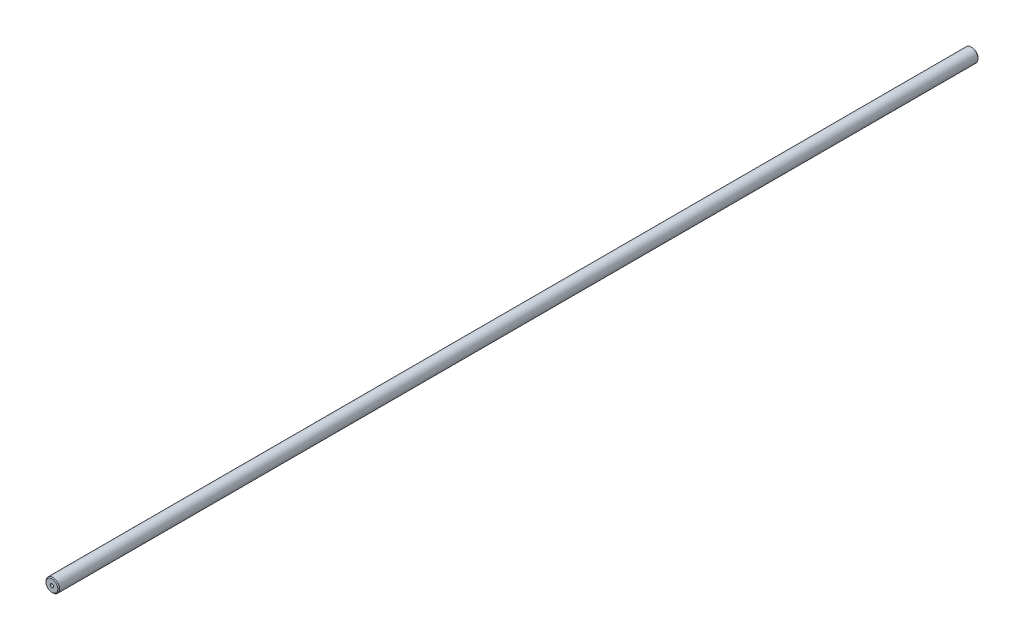
SolidWorks part; units mm, degrees
ref_plane "Front Plane" through (0, 0, 0) normal (0, 0, 1) x (1, 0, 0)
ref_plane "Top Plane" through (0, 0, 0) normal (0, 1, 0) x (1, 0, 0)
ref_plane "Right Plane" through (0, 0, 0) normal (1, 0, 0) x (0, 0, -1)
sketch "Sketch1" plane through (0, 0, 0) normal (0, 0, 1) x (1, 0, 0)
  circle A0 centre (0, 0) radius 4
  dimension "D1" = 8
extrude "Boss-Extrude1" add sketch "Sketch1" along normal blind 544
sketch "Sketch2" plane through (0, 0, 544) normal (0, 0, 1) x (1, 0, 0)
  circle A0 centre (0, 0) radius 1
  dimension "D1" = 2
extrude "Cut-Extrude1" cut sketch "Sketch2" against normal blind 10
chamfer "Chamfer1" distance 0.5 angle 45 2 edges at (4, 0, 0) (4, 0, 544)
